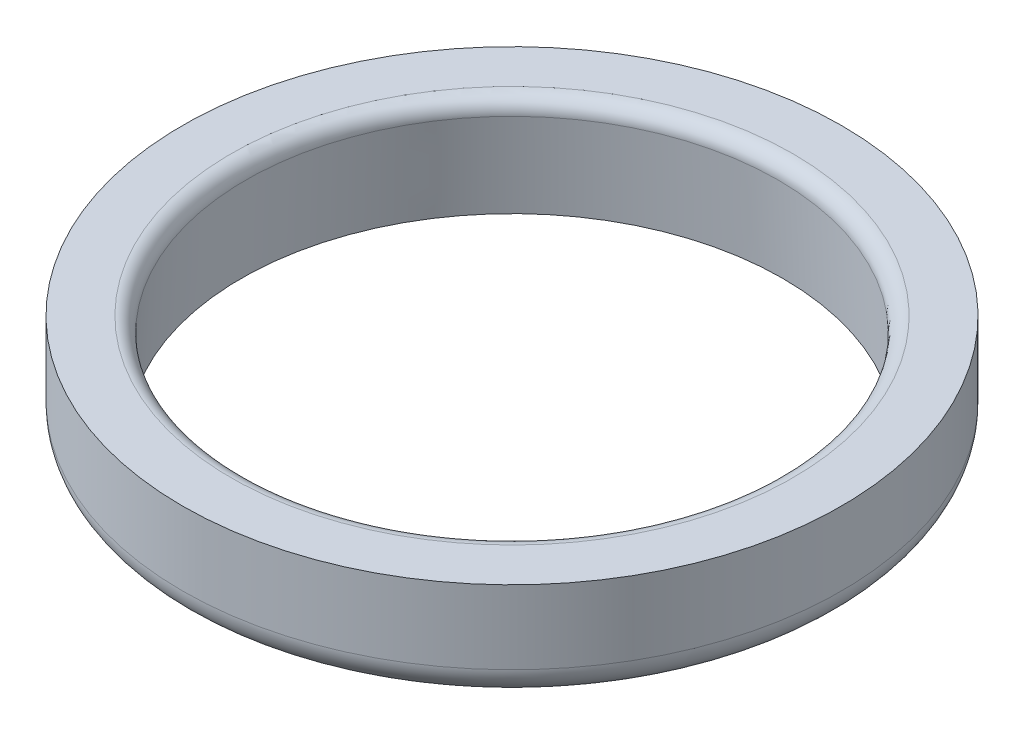
SolidWorks part; units mm, degrees
ref_plane "Front Plane" through (0, 0, 0) normal (0, 0, 1) x (1, 0, 0)
ref_plane "Top Plane" through (0, 0, 0) normal (0, 1, 0) x (1, 0, 0)
ref_plane "Right Plane" through (0, 0, 0) normal (1, 0, 0) x (0, 0, -1)
sketch "Sketch1" plane through (0, 0, 0) normal (0, 0, 1) x (1, 0, 0)
  line L0 (0, 0) -> (0, 5.2283) construction
  line L1 (-4.6, 0.139) -> (-4.5083, 1.889)
  line L2 (-5.6, 0.139) -> (-4.6, 0.139)
  line L3 (-5.6, 0.139) -> (-5.6, 1.889)
  line L4 (-5.6, 1.889) -> (-4.6, 1.889)
  line L6 (-4.6, 1.889) -> (-4.5083, 1.889)
  dimension "D1" = 3
  dimension "D2" = 1
  dimension "D3" = 1.75
revolve "Revolve1" add sketch "Sketch1" angle 360 about L0
fillet "Fillet1" radius 0.5 1 edges at (0, 0.139, -5.6)
fillet "Fillet2" radius 0.25 1 edges at (0, 1.889, -4.5083)
